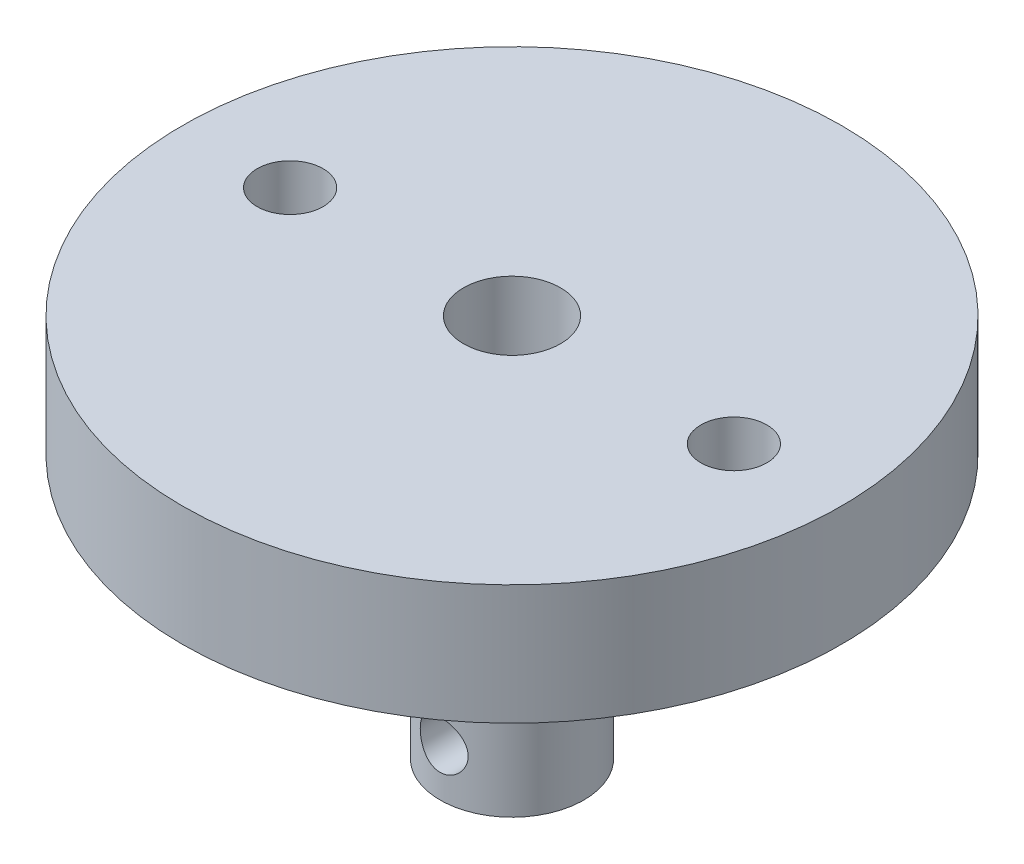
SolidWorks part; units mm, degrees
ref_plane "前视基准面" through (0, 0, 0) normal (0, 0, 1) x (1, 0, 0)
ref_plane "上视基准面" through (0, 0, 0) normal (0, 1, 0) x (1, 0, 0)
ref_plane "右视基准面" through (0, 0, 0) normal (1, 0, 0) x (0, 0, -1)
sketch "草图1" plane through (0, 0, 0) normal (0, 1, 0) x (1, 0, 0)
  circle A0 centre (0, 0) radius 27.5
  dimension "D1" = 55
extrude "凸台-拉伸1" add sketch "草图1" along normal blind 10
sketch "草图2" plane through (0, 0, 0) normal (0, -1, 0) x (1, 0, 0)
  circle A0 centre (18.515, 0) radius 2.75
  dimension "D1" = 5.5
  dimension "D2" = 18.515
extrude "切除-拉伸1" cut sketch "草图2" against normal blind 10
pattern_circular "阵列(圆周)1" count 2 over 360 about axis through (0, 0, 0) along (0, 1, 0) of "切除-拉伸1"
sketch "草图3" plane through (0, 0, 0) normal (0, -1, 0) x (1, 0, 0)
  circle A0 centre (0, 0) radius 6
  dimension "D1" = 12
extrude "凸台-拉伸2" add sketch "草图3" along normal blind 22
sketch "草图5" plane through (0, -22, 0) normal (0, -1, 0) x (1, 0, 0)
  circle A0 centre (0, 0) radius 3.15
  dimension "D1" = 6.3
extrude "切除-拉伸3" cut sketch "草图5" against normal blind 12
sketch "草图4" plane through (0, 10, 0) normal (0, 1, 0) x (1, 0, 0)
  circle A0 centre (0, 0) radius 4.05
  dimension "D1" = 8.1
extrude "切除-拉伸2" cut sketch "草图4" against normal blind 15
sketch "草图6" plane through (0, 0, 0) normal (0, 0, 1) x (1, 0, 0)
  line L0 (-6, -22) -> (6, -22) construction
  circle A0 centre (0, -18) radius 2
  dimension "D2" = 4
  dimension "D1" = 4
extrude "切除-拉伸4" cut sketch "草图6" against normal through all both and the other way through all
